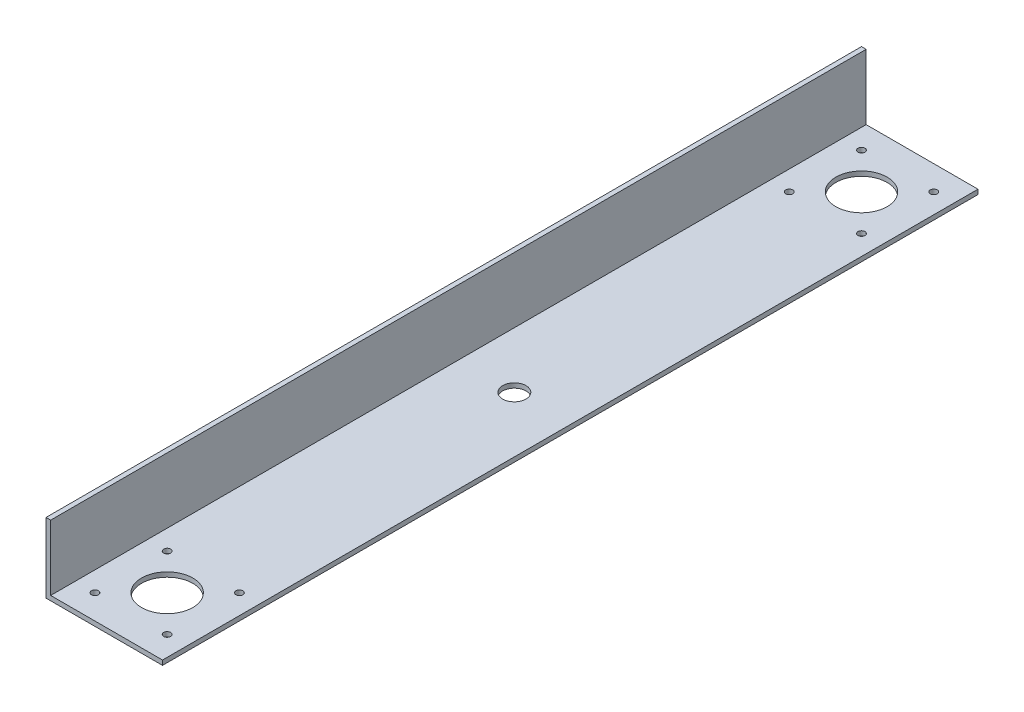
SolidWorks part; units mm, degrees
ref_plane "Front Plane" through (0, 0, 0) normal (0, 0, 1) x (1, 0, 0)
ref_plane "Top Plane" through (0, 0, 0) normal (0, 1, 0) x (1, 0, 0)
ref_plane "Right Plane" through (0, 0, 0) normal (1, 0, 0) x (0, 0, -1)
sketch "Sketch1" plane through (0, 0, 0) normal (0, 0, 1) x (1, 0, 0)
  line L0 (0, 0) -> (0, 30)
  line L1 (0, 30) -> (2, 30)
  line L2 (2, 30) -> (2, 2)
  line L3 (2, 2) -> (50, 2)
  line L4 (50, 2) -> (50, 0)
  line L5 (50, 0) -> (0, 0)
extrude "Boss-Extrude1" add sketch "Sketch1" along normal blind 350
sketch "Sketch6" plane through (0, 2, 0) normal (0, 1, 0) x (1, 0, 0)
  circle A0 centre (41.5, -339.5) radius 1.5
  circle A1 centre (10.5, -308.5) radius 1.5
  circle A2 centre (10.5, -339.5) radius 1.5
  circle A3 centre (41.5, -308.5) radius 1.5
extrude "Cut-Extrude3" cut sketch "Sketch6" against normal through all
sketch "Sketch7" plane through (0, 2, 0) normal (0, 1, 0) x (1, 0, 0)
  circle A0 centre (26, -324) radius 11
extrude "Cut-Extrude4" cut sketch "Sketch7" against normal through all
sketch "Sketch8" plane through (0, 0, 0) normal (0, -1, 0) x (-1, 0, 0)
  circle A0 centre (-26, -26) radius 11
extrude "Cut-Extrude5" cut sketch "Sketch8" against normal through all
sketch "Sketch9" plane through (0, 0, 0) normal (0, -1, 0) x (1, 0, 0)
  circle A0 centre (41.5, 41.5) radius 1.5
  circle A1 centre (10.5, 41.5) radius 1.5
  circle A2 centre (10.5, 10.5) radius 1.5
  circle A3 centre (41.5, 10.5) radius 1.5
extrude "Cut-Extrude6" cut sketch "Sketch9" against normal through all
sketch "Sketch10" plane through (0, 0, 0) normal (0, -1, 0) x (1, 0, 0)
  circle A0 centre (26, 175) radius 5
extrude "Cut-Extrude7" cut sketch "Sketch10" against normal through all
